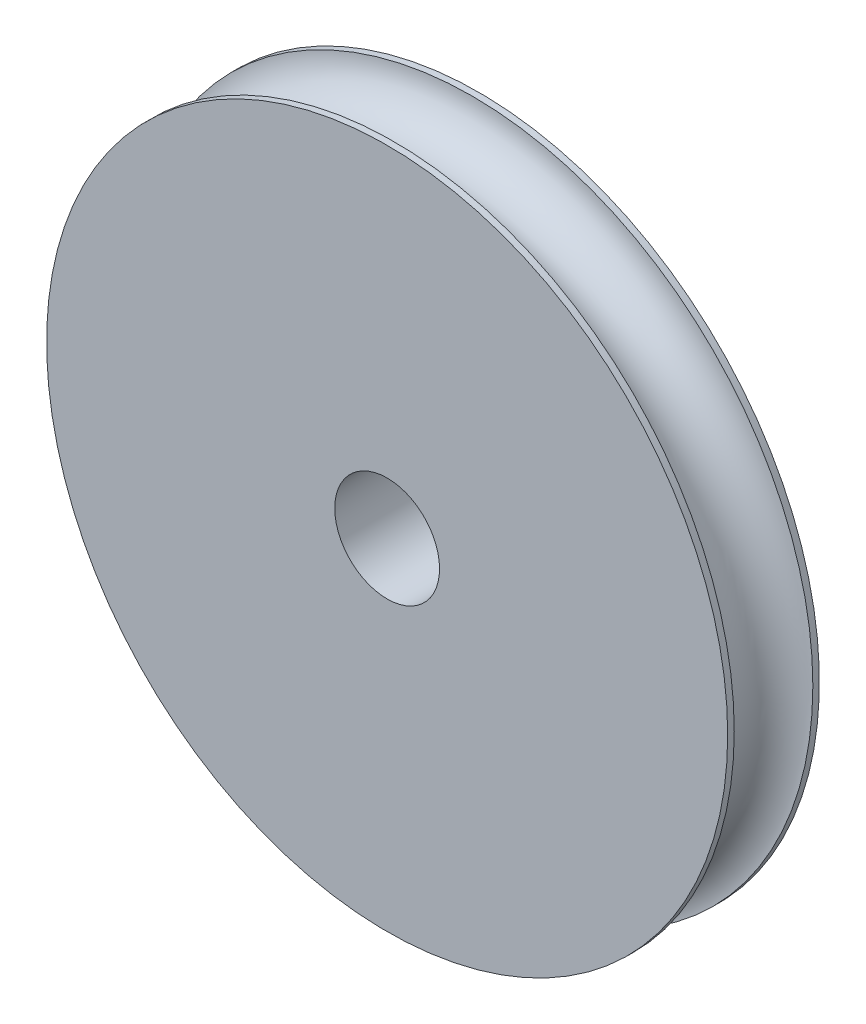
SolidWorks part; units mm, degrees
ref_plane "Front Plane" through (0, 0, 0) normal (0, 0, 1) x (1, 0, 0)
ref_plane "Top Plane" through (0, 0, 0) normal (0, 1, 0) x (1, 0, 0)
ref_plane "Right Plane" through (0, 0, 0) normal (1, 0, 0) x (0, 0, -1)
sketch "Sketch1" plane through (0, 0, 0) normal (0, 1, 0) x (1, 0, 0)
  line L0 (23, 0) -> (35.6534, 0) construction
  line L1 (0, 0) -> (23, 0)
  line L2 (0, 0) -> (0, 6)
  line L3 (0, 6) -> (23, 6)
  line L4 (23, 0) -> (23, 6)
  line L5 (23, 6) -> (36.1226, 6) construction
  line L6 (23, 6) -> (26, 6)
  line L7 (23, 0) -> (26, 0)
  circle A0 centre (26, 3) radius 3
revolve "Revolve1" add sketch "Sketch1" angle 360 about L2
sketch "Sketch2" plane through (0, 0, 0) normal (0, 0, 1) x (1, 0, 0)
  circle A0 centre (0, 0) radius 1
  circle A1 centre (0, 0) radius 26
extrude "Boss-Extrude1" add sketch "Sketch2" along normal blind 0.5
sketch "Sketch3" plane through (0, 0, -6) normal (0, 0, -1) x (-1, 0, 0)
  circle A0 centre (0, 0) radius 26
extrude "Boss-Extrude2" add sketch "Sketch3" along normal blind 0.5
sketch "Sketch4" plane through (0, 0, -6.5) normal (0, 0, -1) x (-1, 0, 0)
  circle A0 centre (0, 0) radius 1
extrude "Cut-Extrude2" cut sketch "Sketch4" against normal up to surface (7 mm away) up to face at (26, 0, 0.5)
sketch "Sketch5" plane through (0, 0, -6.5) normal (0, 0, -1) x (-1, 0, 0)
  circle A0 centre (0, 0) radius 4
extrude "Cut-Extrude3" cut sketch "Sketch5" against normal blind 10
